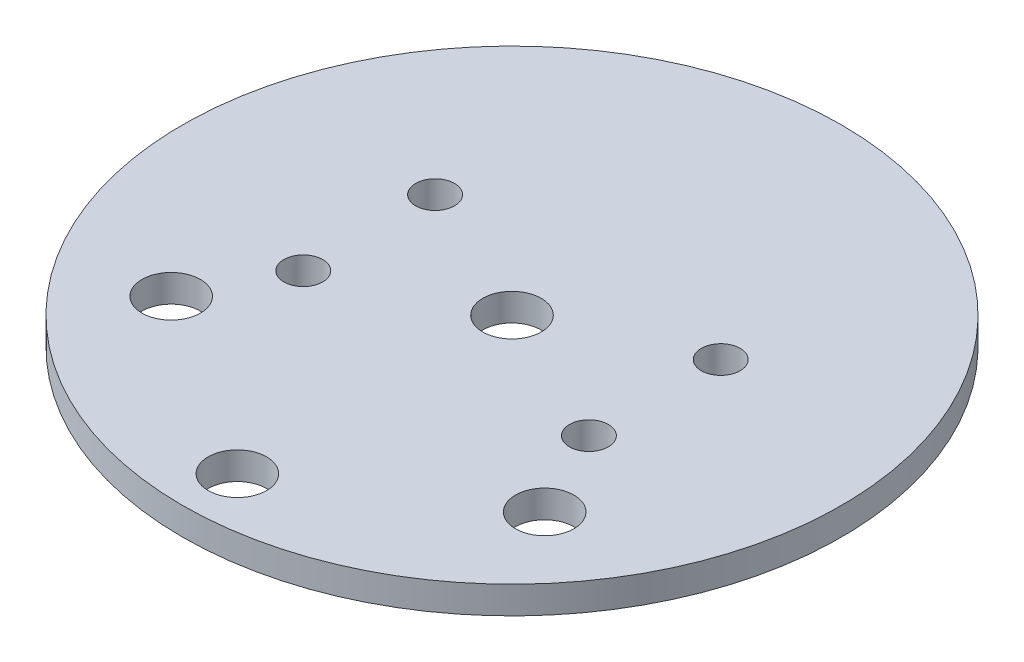
SolidWorks part; units mm, degrees
ref_plane "Front Plane" through (0, 0, 0) normal (0, 0, 1) x (1, 0, 0)
ref_plane "Top Plane" through (0, 0, 0) normal (0, 1, 0) x (1, 0, 0)
ref_plane "Right Plane" through (0, 0, 0) normal (1, 0, 0) x (0, 0, -1)
sketch "Sketch1" plane through (0, 0, 0) normal (0, 1, 0) x (1, 0, 0)
  circle A0 centre (0, 0) radius 38.1
  dimension "D1" = 76.2
extrude "Boss-Extrude1" add sketch "Sketch1" along normal mid plane 3.175 contours A0
sketch "Sketch2" plane through (0, 0, 0) normal (0, 1, 0) x (1, 0, 0)
  line L0 (-35.9958, -12.4865) -> (35.9958, -12.4865)
  line L1 (-30.2719, -23.1349) -> (30.2719, -23.1349)
  line L2 (-21.59, -12.4865) -> (-21.59, -23.1349) construction
  line L3 (0, -1.7463) -> (0, 1.7463) construction
  line L4 (-1.7463, 0) -> (1.7463, 0) construction
  circle A0 centre (0, 0) radius 38.1 construction
  point P4 (0, -12.4865)
  point P8 (0, -23.1349)
  point P13 (-21.59, -17.8107)
  point P14 (0, -31.75)
  point P15 (21.59, -17.8107)
  point P16 (-16.51, 7.62)
  point P17 (16.51, 7.62)
  point P18 (-16.51, -7.62)
  point P19 (16.51, -7.62)
  dimension "D1" = 12.4865
  dimension "D2" = 23.1349
  dimension "D3" = 21.59
  dimension "D4" = 31.75
  dimension "D5" = 7.62
  dimension "D6" = 7.62
  dimension "D7" = 7.62
  dimension "D8" = 7.62
  dimension "D9" = 16.51
  dimension "D10" = 16.51
  dimension "D11" = 16.51
  dimension "D12" = 16.51
hole_wizard "1/4 Clearance Hole1" positions "Sketch3" profile "Sketch4" hole size "1/4" standard "ANSI Inch" end condition through all
sketch "Sketch3" plane through (0, 1.5875, 0) normal (0, 1, 0) x (1, 0, 0)
  point P0 (-21.59, -17.8107)
  point P3 (21.59, -17.8107)
sketch "Sketch4" plane through (-21.59, 1.5875, 17.8107) normal (1, 0, 0) x (0, 0, 1)
  line L0 (0, 0) -> (0, 3.175)
  line L1 (0, 3.175) -> (3.3782, 3.175)
  line L2 (3.3782, 3.175) -> (3.3782, 0)
  line L5 (3.3782, 0) -> (0, 0)
  line L11 (0, -6.35) -> (0, 107.95) construction
  dimension "Thru Hole Dia." = 6.7564
  dimension "Thru Hole Depth" = 3.175
hole_wizard "1/4 Clearance Hole2" positions "Sketch5" profile "Sketch6" hole size "1/4" standard "ANSI Inch" end condition through all
sketch "Sketch5" plane through (0, 1.5875, 0) normal (0, 1, 0) x (1, 0, 0)
  point P0 (0, 0)
sketch "Sketch6" plane through (0, 1.5875, 0) normal (1, 0, 0) x (0, 0, 1)
  line L0 (0, 0) -> (0, 3.175)
  line L1 (0, 3.175) -> (3.3782, 3.175)
  line L2 (3.3782, 3.175) -> (3.3782, 0)
  line L5 (3.3782, 0) -> (0, 0)
  line L11 (0, -6.35) -> (0, 107.95) construction
  dimension "Thru Hole Dia." = 6.7564
  dimension "Thru Hole Depth" = 3.175
hole_wizard "1/4 Clearance Hole3" positions "Sketch7" profile "Sketch8" hole size "1/4" standard "ANSI Inch" end condition through all
sketch "Sketch7" plane through (0, 1.5875, 0) normal (0, 1, 0) x (1, 0, 0)
  point P0 (0, -31.75)
sketch "Sketch8" plane through (0, 1.5875, 31.75) normal (1, 0, 0) x (0, 0, 1)
  line L0 (0, 0) -> (0, 3.175)
  line L1 (0, 3.175) -> (3.3782, 3.175)
  line L2 (3.3782, 3.175) -> (3.3782, 0)
  line L5 (3.3782, 0) -> (0, 0)
  line L11 (0, -6.35) -> (0, 107.95) construction
  dimension "Thru Hole Dia." = 6.7564
  dimension "Thru Hole Depth" = 3.175
hole_wizard "#8 Clearance Hole1" positions "Sketch9" profile "Sketch10" hole size "#8" standard "ANSI Inch" end condition through all
sketch "Sketch9" plane through (0, 1.5875, 0) normal (0, 1, 0) x (1, 0, 0)
  point P0 (-16.51, 7.62)
  point P3 (-16.51, -7.62)
  point P6 (16.51, -7.62)
  point P9 (16.51, 7.62)
sketch "Sketch10" plane through (-16.51, 1.5875, -7.62) normal (1, 0, 0) x (0, 0, 1)
  line L0 (0, 0) -> (0, 3.175)
  line L1 (0, 3.175) -> (2.2479, 3.175)
  line L2 (2.2479, 3.175) -> (2.2479, 0)
  line L5 (2.2479, 0) -> (0, 0)
  line L11 (0, -6.35) -> (0, 107.95) construction
  dimension "Thru Hole Dia." = 4.4958
  dimension "Thru Hole Depth" = 3.175
